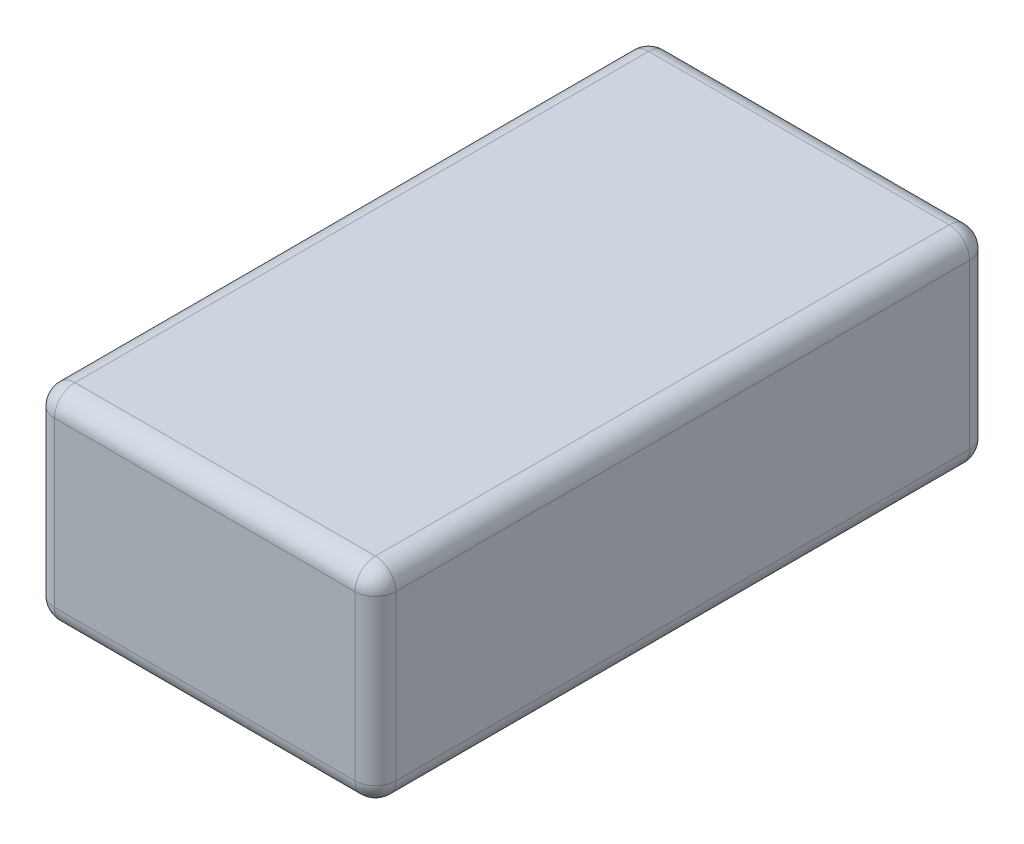
SolidWorks part; units mm, degrees
ref_plane "Front Plane" through (0, 0, 0) normal (0, 0, 1) x (1, 0, 0)
ref_plane "Top Plane" through (0, 0, 0) normal (0, 1, 0) x (1, 0, 0)
ref_plane "Right Plane" through (0, 0, 0) normal (1, 0, 0) x (0, 0, -1)
sketch "Sketch1" plane through (0, 3, 0) normal (0, 1, 0) x (1, 0, 0)
  line L1 (-36.6379, 22.9426) -> (-11.6379, 22.9426)
  line L2 (-36.6379, 22.9426) -> (-36.6379, -22.0574)
  line L3 (-36.6379, -22.0574) -> (-11.6379, -22.0574)
  line L4 (-11.6379, 22.9426) -> (-11.6379, -22.0574)
  dimension "D1" = 45
  dimension "D2" = 25
extrude "Boss-Extrude1" add sketch "Sketch1" along normal blind 15
fillet "Fillet1" radius 1.5 12 edges at (-36.6379, 3, -0.4426) (-36.6379, 10.5, -22.9426) (-24.1379, 3, -22.9426) (-11.6379, 10.5, -22.9426) (-11.6379, 3, -0.4426) (-24.1379, 3, 22.0574) (-11.6379, 10.5, 22.0574) (-36.6379, 10.5, 22.0574) (-11.6379, 18, -0.4426) (-36.6379, 18, -0.4426) (-24.1379, 18, -22.9426) (-24.1379, 18, 22.0574)
